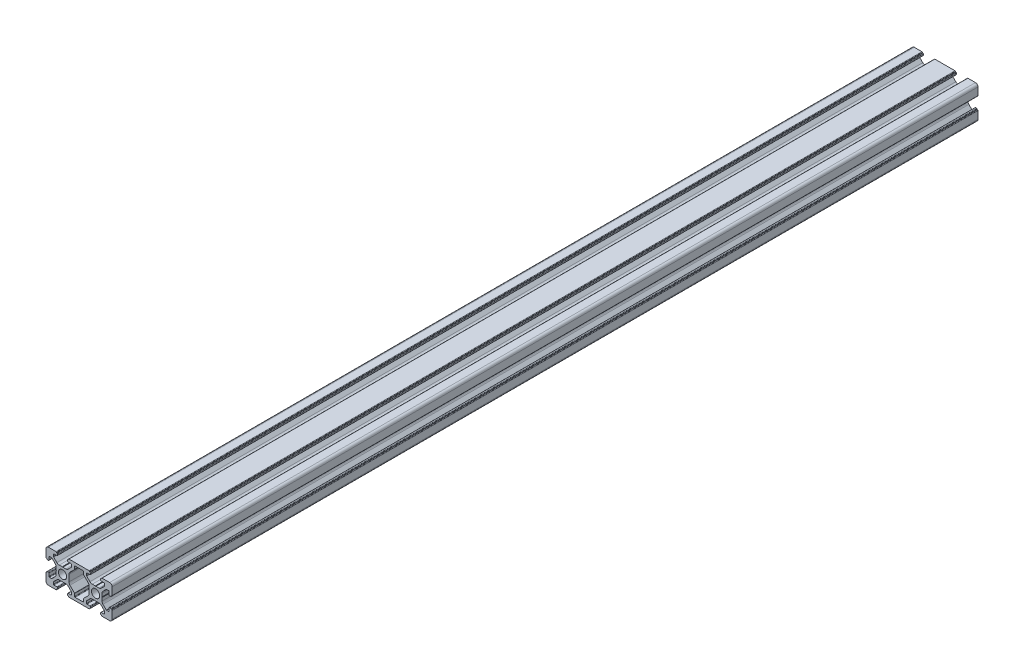
SolidWorks part; units mm, degrees
ref_plane "前视基准面" through (0, 0, 0) normal (0, 0, 1) x (1, 0, 0)
ref_plane "上视基准面" through (0, 0, 0) normal (0, 1, 0) x (1, 0, 0)
ref_plane "右视基准面" through (0, 0, 0) normal (1, 0, 0) x (0, 0, -1)
sketch "草图1" plane through (0, 0, 0) normal (0, 0, 1) x (1, 0, 0)
  line L0 (-2.7, -6.3636) -> (-2.7, -7.9)
  line L1 (-5.5142, -3.4251) -> (-2.7879, -6.1515)
  line L2 (-2.4, -8.2) -> (2.4, -8.2)
  line L3 (-6.1, 0) -> (-6.1, -2.0109)
  line L4 (-6.1, 2.0109) -> (-6.1, 0)
  line L5 (2.7, -6.3636) -> (2.7, -7.9)
  line L6 (-2.7879, 6.1515) -> (-5.5142, 3.4251)
  line L7 (5.5142, -3.4251) -> (2.7879, -6.1515)
  line L8 (-2.7, 6.3636) -> (-2.7, 7.9)
  line L9 (6.1, 0) -> (6.1, -2.0109)
  line L10 (6.1, 2.0109) -> (6.1, 0)
  line L11 (-2.4, 8.2) -> (2.4, 8.2)
  line L12 (2.7879, 6.1515) -> (5.5142, 3.4251)
  line L13 (2.7, 6.3636) -> (2.7, 7.9)
  line L14 (4.5, -6.6849) -> (4.5, -7.9)
  line L15 (4.8, -8.2) -> (6.6, -8.2)
  line L16 (6.9, -8.5) -> (6.9, -9.2)
  line L17 (6.6, -9.5) -> (6.4, -9.5)
  line L18 (6.4, -9.5) -> (6.4, -9.7)
  line L19 (6.1, -10) -> (-6.1, -10)
  line L20 (-6.4, -9.7) -> (-6.4, -9.5)
  line L21 (-6.4, -9.5) -> (-6.6, -9.5)
  line L22 (-6.9, -9.2) -> (-6.9, -8.5)
  line L23 (-6.6, -8.2) -> (-4.8, -8.2)
  line L24 (-4.5, -7.9) -> (-4.5, -6.6849)
  line L25 (-4.5879, -6.4728) -> (-6.5749, -4.4858)
  line L26 (-7.9891, -3.9) -> (-9.8, -3.9)
  line L27 (-9.8, -3.9) -> (-10, -3.7)
  line L28 (-10, -3.7) -> (-10.2, -3.9)
  line L29 (-10.2, -3.9) -> (-12.0109, -3.9)
  line L30 (-13.4251, -4.4858) -> (-15.4121, -6.4728)
  line L31 (-15.5, -6.6849) -> (-15.5, -7.9)
  line L32 (-15.2, -8.2) -> (-13.4, -8.2)
  line L33 (-13.1, -8.5) -> (-13.1, -9.2)
  line L34 (-13.4, -9.5) -> (-13.6, -9.5)
  line L35 (-13.6, -9.5) -> (-13.6, -9.7)
  line L36 (-13.9, -10) -> (-18.5, -10)
  line L37 (-20, -8.5) -> (-20, -3.9)
  line L38 (-19.7, -3.6) -> (-19.5, -3.6)
  line L39 (-19.5, -3.6) -> (-19.5, -3.4)
  line L40 (-19.2, -3.1) -> (-18.5, -3.1)
  line L41 (-18.2, -3.4) -> (-18.2, -5.2)
  line L42 (-17.9, -5.5) -> (-16.6849, -5.5)
  line L43 (-16.4728, -5.4121) -> (-14.4858, -3.4251)
  line L44 (-13.9, -2.0109) -> (-13.9, -0.2)
  line L45 (-13.9, -0.2) -> (-13.7, 0)
  line L46 (-13.7, 0) -> (-13.9, 0.2)
  line L47 (-13.9, 0.2) -> (-13.9, 2.0109)
  line L48 (-14.4858, 3.4251) -> (-16.4728, 5.4121)
  line L49 (-16.6849, 5.5) -> (-17.9, 5.5)
  line L50 (-18.2, 5.2) -> (-18.2, 3.4)
  line L51 (-18.5, 3.1) -> (-19.2, 3.1)
  line L52 (-19.5, 3.4) -> (-19.5, 3.6)
  line L53 (-19.5, 3.6) -> (-19.7, 3.6)
  line L54 (-20, 3.9) -> (-20, 8.5)
  line L55 (-18.5, 10) -> (-13.9, 10)
  line L56 (-13.6, 9.7) -> (-13.6, 9.5)
  line L57 (-13.6, 9.5) -> (-13.4, 9.5)
  line L58 (-13.1, 9.2) -> (-13.1, 8.5)
  line L59 (-13.4, 8.2) -> (-15.2, 8.2)
  line L60 (-15.5, 7.9) -> (-15.5, 6.6849)
  line L61 (-15.4121, 6.4728) -> (-13.4251, 4.4858)
  line L62 (-12.0109, 3.9) -> (-10.2, 3.9)
  line L63 (-10.2, 3.9) -> (-10, 3.7)
  line L64 (-10, 3.7) -> (-9.8, 3.9)
  line L65 (-9.8, 3.9) -> (-7.9891, 3.9)
  line L66 (-6.5749, 4.4858) -> (-4.5879, 6.4728)
  line L67 (-4.5, 6.6849) -> (-4.5, 7.9)
  line L68 (-4.8, 8.2) -> (-6.6, 8.2)
  line L69 (-6.9, 8.5) -> (-6.9, 9.2)
  line L70 (-6.6, 9.5) -> (-6.4, 9.5)
  line L71 (-6.4, 9.5) -> (-6.4, 9.7)
  line L72 (-6.1, 10) -> (6.1, 10)
  line L73 (6.4, 9.7) -> (6.4, 9.5)
  line L74 (6.4, 9.5) -> (6.6, 9.5)
  line L75 (6.9, 9.2) -> (6.9, 8.5)
  line L76 (6.6, 8.2) -> (4.8, 8.2)
  line L77 (4.5, 7.9) -> (4.5, 6.6849)
  line L78 (4.5879, 6.4728) -> (6.5749, 4.4858)
  line L79 (7.9891, 3.9) -> (9.8, 3.9)
  line L80 (9.8, 3.9) -> (10, 3.7)
  line L81 (10, 3.7) -> (10.2, 3.9)
  line L82 (10.2, 3.9) -> (12.0109, 3.9)
  line L83 (13.4251, 4.4858) -> (15.4121, 6.4728)
  line L84 (15.5, 6.6849) -> (15.5, 7.9)
  line L85 (15.2, 8.2) -> (13.4, 8.2)
  line L86 (13.1, 8.5) -> (13.1, 9.2)
  line L87 (13.4, 9.5) -> (13.6, 9.5)
  line L88 (13.6, 9.5) -> (13.6, 9.7)
  line L89 (13.9, 10) -> (18.5, 10)
  line L90 (20, 8.5) -> (20, 3.9)
  line L91 (19.7, 3.6) -> (19.5, 3.6)
  line L92 (19.5, 3.6) -> (19.5, 3.4)
  line L93 (19.2, 3.1) -> (18.5, 3.1)
  line L94 (18.2, 3.4) -> (18.2, 5.2)
  line L95 (17.9, 5.5) -> (16.6849, 5.5)
  line L96 (16.4728, 5.4121) -> (14.4858, 3.4251)
  line L97 (13.9, 2.0109) -> (13.9, 0.2)
  line L98 (13.9, 0.2) -> (13.7, 0)
  line L99 (13.7, 0) -> (13.9, -0.2)
  line L100 (13.9, -0.2) -> (13.9, -2.0109)
  line L101 (14.4858, -3.4251) -> (16.4728, -5.4121)
  line L102 (16.6849, -5.5) -> (17.9, -5.5)
  line L103 (18.2, -5.2) -> (18.2, -3.4)
  line L104 (18.5, -3.1) -> (19.2, -3.1)
  line L105 (19.5, -3.4) -> (19.5, -3.6)
  line L106 (19.5, -3.6) -> (19.7, -3.6)
  line L107 (20, -3.9) -> (20, -8.5)
  line L108 (18.5, -10) -> (13.9, -10)
  line L109 (13.6, -9.7) -> (13.6, -9.5)
  line L110 (13.6, -9.5) -> (13.4, -9.5)
  line L111 (13.1, -9.2) -> (13.1, -8.5)
  line L112 (13.4, -8.2) -> (15.2, -8.2)
  line L113 (15.5, -7.9) -> (15.5, -6.6849)
  line L114 (15.4121, -6.4728) -> (13.4251, -4.4858)
  line L115 (12.0109, -3.9) -> (10.2, -3.9)
  line L116 (10.2, -3.9) -> (10, -3.7)
  line L117 (10, -3.7) -> (9.8, -3.9)
  line L118 (9.8, -3.9) -> (7.9891, -3.9)
  line L119 (6.5749, -4.4858) -> (4.5879, -6.4728)
  arc A0 (-2.7, -6.3636) -> (-2.7879, -6.1515) centre (-3, -6.3636) ccw
  arc A1 (-2.7, -7.9) -> (-2.4, -8.2) centre (-2.4, -7.9) ccw
  arc A2 (-6.1, -2.0109) -> (-5.5142, -3.4251) centre (-4.1, -2.0109) ccw
  arc A3 (2.4, -8.2) -> (2.7, -7.9) centre (2.4, -7.9) ccw
  arc A4 (-5.5142, 3.4251) -> (-6.1, 2.0109) centre (-4.1, 2.0109) ccw
  arc A5 (2.7879, -6.1515) -> (2.7, -6.3636) centre (3, -6.3636) ccw
  arc A6 (-2.7879, 6.1515) -> (-2.7, 6.3636) centre (-3, 6.3636) ccw
  arc A7 (5.5142, -3.4251) -> (6.1, -2.0109) centre (4.1, -2.0109) ccw
  arc A8 (-2.4, 8.2) -> (-2.7, 7.9) centre (-2.4, 7.9) ccw
  arc A9 (6.1, 2.0109) -> (5.5142, 3.4251) centre (4.1, 2.0109) ccw
  arc A10 (2.7, 7.9) -> (2.4, 8.2) centre (2.4, 7.9) ccw
  arc A11 (2.7, 6.3636) -> (2.7879, 6.1515) centre (3, 6.3636) ccw
  arc A12 (4.5, -7.9) -> (4.8, -8.2) centre (4.8, -7.9) ccw
  arc A13 (6.9, -8.5) -> (6.6, -8.2) centre (6.6, -8.5) ccw
  arc A14 (6.6, -9.5) -> (6.9, -9.2) centre (6.6, -9.2) ccw
  arc A15 (6.1, -10) -> (6.4, -9.7) centre (6.1, -9.7) ccw
  arc A16 (-6.4, -9.7) -> (-6.1, -10) centre (-6.1, -9.7) ccw
  arc A17 (-6.9, -9.2) -> (-6.6, -9.5) centre (-6.6, -9.2) ccw
  arc A18 (-6.6, -8.2) -> (-6.9, -8.5) centre (-6.6, -8.5) ccw
  arc A19 (-4.8, -8.2) -> (-4.5, -7.9) centre (-4.8, -7.9) ccw
  arc A20 (-4.5, -6.6849) -> (-4.5879, -6.4728) centre (-4.8, -6.6849) ccw
  arc A21 (-6.5749, -4.4858) -> (-7.9891, -3.9) centre (-7.9891, -5.9) ccw
  arc A22 (-12.0109, -3.9) -> (-13.4251, -4.4858) centre (-12.0109, -5.9) ccw
  arc A23 (-15.4121, -6.4728) -> (-15.5, -6.6849) centre (-15.2, -6.6849) ccw
  arc A24 (-15.5, -7.9) -> (-15.2, -8.2) centre (-15.2, -7.9) ccw
  arc A25 (-13.1, -8.5) -> (-13.4, -8.2) centre (-13.4, -8.5) ccw
  arc A26 (-13.4, -9.5) -> (-13.1, -9.2) centre (-13.4, -9.2) ccw
  arc A27 (-13.9, -10) -> (-13.6, -9.7) centre (-13.9, -9.7) ccw
  arc A28 (-20, -8.5) -> (-18.5, -10) centre (-18.5, -8.5) ccw
  arc A29 (-19.7, -3.6) -> (-20, -3.9) centre (-19.7, -3.9) ccw
  arc A30 (-19.2, -3.1) -> (-19.5, -3.4) centre (-19.2, -3.4) ccw
  arc A31 (-18.2, -3.4) -> (-18.5, -3.1) centre (-18.5, -3.4) ccw
  arc A32 (-18.2, -5.2) -> (-17.9, -5.5) centre (-17.9, -5.2) ccw
  arc A33 (-16.6849, -5.5) -> (-16.4728, -5.4121) centre (-16.6849, -5.2) ccw
  arc A34 (-14.4858, -3.4251) -> (-13.9, -2.0109) centre (-15.9, -2.0109) ccw
  arc A35 (-13.9, 2.0109) -> (-14.4858, 3.4251) centre (-15.9, 2.0109) ccw
  arc A36 (-16.4728, 5.4121) -> (-16.6849, 5.5) centre (-16.6849, 5.2) ccw
  arc A37 (-17.9, 5.5) -> (-18.2, 5.2) centre (-17.9, 5.2) ccw
  arc A38 (-18.5, 3.1) -> (-18.2, 3.4) centre (-18.5, 3.4) ccw
  arc A39 (-19.5, 3.4) -> (-19.2, 3.1) centre (-19.2, 3.4) ccw
  arc A40 (-20, 3.9) -> (-19.7, 3.6) centre (-19.7, 3.9) ccw
  arc A41 (-18.5, 10) -> (-20, 8.5) centre (-18.5, 8.5) ccw
  arc A42 (-13.6, 9.7) -> (-13.9, 10) centre (-13.9, 9.7) ccw
  arc A43 (-13.1, 9.2) -> (-13.4, 9.5) centre (-13.4, 9.2) ccw
  arc A44 (-13.4, 8.2) -> (-13.1, 8.5) centre (-13.4, 8.5) ccw
  arc A45 (-15.2, 8.2) -> (-15.5, 7.9) centre (-15.2, 7.9) ccw
  arc A46 (-15.5, 6.6849) -> (-15.4121, 6.4728) centre (-15.2, 6.6849) ccw
  arc A47 (-13.4251, 4.4858) -> (-12.0109, 3.9) centre (-12.0109, 5.9) ccw
  arc A48 (-7.9891, 3.9) -> (-6.5749, 4.4858) centre (-7.9891, 5.9) ccw
  arc A49 (-4.5879, 6.4728) -> (-4.5, 6.6849) centre (-4.8, 6.6849) ccw
  arc A50 (-4.5, 7.9) -> (-4.8, 8.2) centre (-4.8, 7.9) ccw
  arc A51 (-6.9, 8.5) -> (-6.6, 8.2) centre (-6.6, 8.5) ccw
  arc A52 (-6.6, 9.5) -> (-6.9, 9.2) centre (-6.6, 9.2) ccw
  arc A53 (-6.1, 10) -> (-6.4, 9.7) centre (-6.1, 9.7) ccw
  arc A54 (6.4, 9.7) -> (6.1, 10) centre (6.1, 9.7) ccw
  arc A55 (6.9, 9.2) -> (6.6, 9.5) centre (6.6, 9.2) ccw
  arc A56 (6.6, 8.2) -> (6.9, 8.5) centre (6.6, 8.5) ccw
  arc A57 (4.8, 8.2) -> (4.5, 7.9) centre (4.8, 7.9) ccw
  arc A58 (4.5, 6.6849) -> (4.5879, 6.4728) centre (4.8, 6.6849) ccw
  arc A59 (6.5749, 4.4858) -> (7.9891, 3.9) centre (7.9891, 5.9) ccw
  arc A60 (12.0109, 3.9) -> (13.4251, 4.4858) centre (12.0109, 5.9) ccw
  arc A61 (15.4121, 6.4728) -> (15.5, 6.6849) centre (15.2, 6.6849) ccw
  arc A62 (15.5, 7.9) -> (15.2, 8.2) centre (15.2, 7.9) ccw
  arc A63 (13.1, 8.5) -> (13.4, 8.2) centre (13.4, 8.5) ccw
  arc A64 (13.4, 9.5) -> (13.1, 9.2) centre (13.4, 9.2) ccw
  arc A65 (13.9, 10) -> (13.6, 9.7) centre (13.9, 9.7) ccw
  arc A66 (20, 8.5) -> (18.5, 10) centre (18.5, 8.5) ccw
  arc A67 (19.7, 3.6) -> (20, 3.9) centre (19.7, 3.9) ccw
  arc A68 (19.2, 3.1) -> (19.5, 3.4) centre (19.2, 3.4) ccw
  arc A69 (18.2, 3.4) -> (18.5, 3.1) centre (18.5, 3.4) ccw
  arc A70 (18.2, 5.2) -> (17.9, 5.5) centre (17.9, 5.2) ccw
  arc A71 (16.6849, 5.5) -> (16.4728, 5.4121) centre (16.6849, 5.2) ccw
  arc A72 (14.4858, 3.4251) -> (13.9, 2.0109) centre (15.9, 2.0109) ccw
  arc A73 (13.9, -2.0109) -> (14.4858, -3.4251) centre (15.9, -2.0109) ccw
  arc A74 (16.4728, -5.4121) -> (16.6849, -5.5) centre (16.6849, -5.2) ccw
  arc A75 (17.9, -5.5) -> (18.2, -5.2) centre (17.9, -5.2) ccw
  arc A76 (18.5, -3.1) -> (18.2, -3.4) centre (18.5, -3.4) ccw
  arc A77 (19.5, -3.4) -> (19.2, -3.1) centre (19.2, -3.4) ccw
  arc A78 (20, -3.9) -> (19.7, -3.6) centre (19.7, -3.9) ccw
  arc A79 (18.5, -10) -> (20, -8.5) centre (18.5, -8.5) ccw
  arc A80 (13.6, -9.7) -> (13.9, -10) centre (13.9, -9.7) ccw
  arc A81 (13.1, -9.2) -> (13.4, -9.5) centre (13.4, -9.2) ccw
  arc A82 (13.4, -8.2) -> (13.1, -8.5) centre (13.4, -8.5) ccw
  arc A83 (15.2, -8.2) -> (15.5, -7.9) centre (15.2, -7.9) ccw
  arc A84 (15.5, -6.6849) -> (15.4121, -6.4728) centre (15.2, -6.6849) ccw
  arc A85 (13.4251, -4.4858) -> (12.0109, -3.9) centre (12.0109, -5.9) ccw
  arc A86 (7.9891, -3.9) -> (6.5749, -4.4858) centre (7.9891, -5.9) ccw
  arc A87 (4.5879, -6.4728) -> (4.5, -6.6849) centre (4.8, -6.6849) ccw
  circle A88 centre (10, 0) radius 2.5
  circle A89 centre (-10, 0) radius 2.5
extrude "凸台-拉伸1" add sketch "草图1" along normal blind 524
